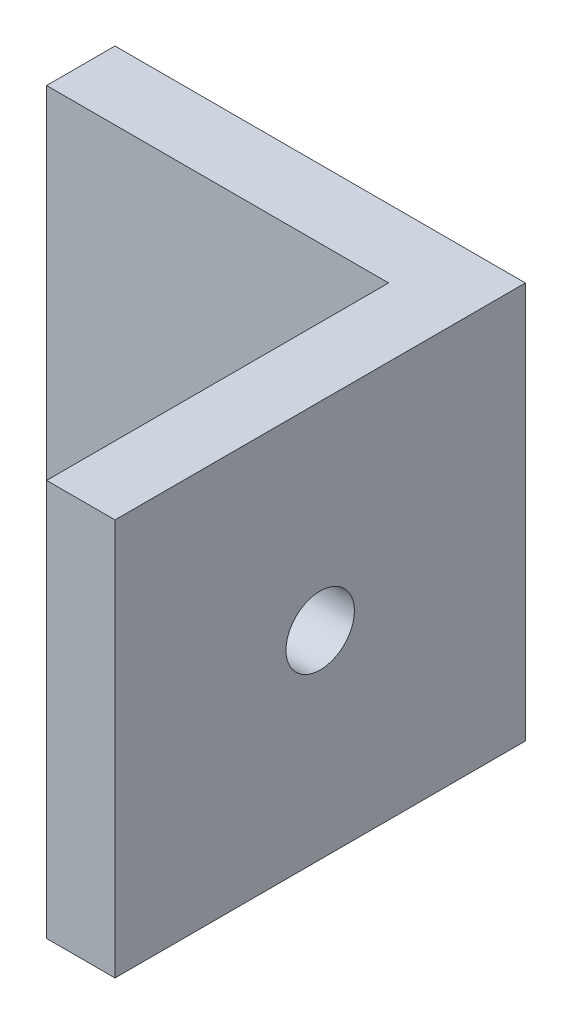
SolidWorks part; units mm, degrees
ref_plane "Front Plane" through (0, 0, 0) normal (0, 0, 1) x (1, 0, 0)
ref_plane "Top Plane" through (0, 0, 0) normal (0, 1, 0) x (1, 0, 0)
ref_plane "Right Plane" through (0, 0, 0) normal (1, 0, 0) x (0, 0, -1)
sketch "Sketch1" plane through (0, 0, 0) normal (0, 1, 0) x (1, 0, 0)
  line L1 (0, 0) -> (38.1, 0)
  line L2 (0, 0) -> (0, 38.1)
  line L3 (0, 38.1) -> (38.1, 38.1)
  line L4 (38.1, 0) -> (38.1, 38.1)
  dimension "D1" = 38.1
  dimension "D2" = 38.1
extrude "Boss-Extrude1" add sketch "Sketch1" along normal blind 36.83
sketch "Sketch2" plane through (0, 36.83, 0) normal (0, 1, 0) x (1, 0, 0)
  line L0 (38.1, 0) -> (38.1, 38.1) construction
  line L1 (0, 38.1) -> (38.1, 38.1)
  line L2 (0, 38.1) -> (0, 31.75)
  line L3 (0, 31.75) -> (38.1, 31.75) construction
  line L4 (38.1, 38.1) -> (38.1, 31.75)
  line L5 (0, 31.75) -> (31.75, 31.75)
  line L6 (31.75, 31.75) -> (38.1, 31.75) construction
  line L7 (31.75, 31.75) -> (31.75, 0)
  line L8 (31.75, 0) -> (38.1, 0)
  line L9 (38.1, 31.75) -> (38.1, 0)
  line L10 (31.75, 0) -> (31.75, 31.75)
  line M10 (0, 38.1) -> (0, 0)
  line M11 (0, 0) -> (38.1, 0)
  dimension "D1" = 6.35
extrude "Cut-Extrude1" cut sketch "Sketch2" against normal through all contours L7 L5 M10 M11
sketch "Sketch3" plane through (0, 0, -31.75) normal (0, 0, 1) x (1, 0, 0)
  line L0 (0, 18.415) -> (31.75, 18.415) construction
  line L3 (0, 0) -> (0, 36.83) construction
  line L4 (31.75, 0) -> (31.75, 36.83) construction
  circle A0 centre (19.05, 18.415) radius 3.175
  point P5 (0, 19.05)
  dimension "D1" = 6.35
  dimension "D2" = 12.7
sketch "Sketch4" plane through (31.75, 0, 0) normal (-1, 0, 0) x (0, 0, 1)
  line L0 (-31.75, 18.415) -> (0, 18.415) construction
  line L1 (-31.75, 0) -> (-31.75, 36.83) construction
  line L2 (0, 0) -> (0, 36.83) construction
  circle A0 centre (-19.05, 18.415) radius 3.175
  dimension "D1" = 6.35
  dimension "D2" = 12.7
extrude "Cut-Extrude2" cut sketch "Sketch4" against normal through all
extrude "Cut-Extrude3" cut sketch "Sketch3" against normal through all contours A0
